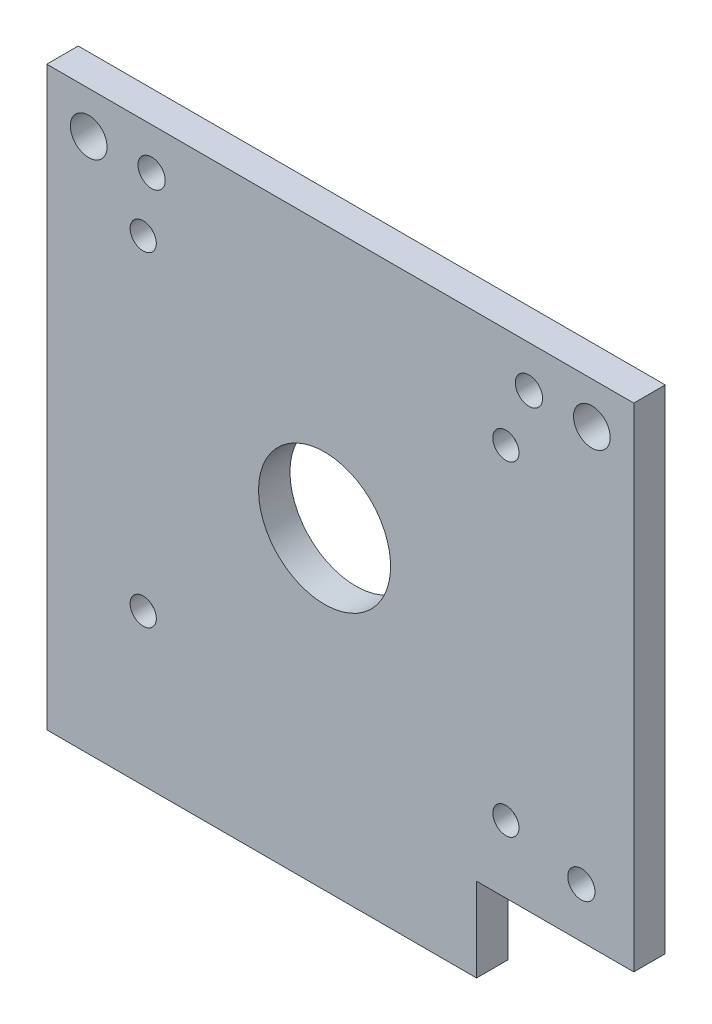
SolidWorks part; units mm, degrees
ref_plane "Alzado" through (0, 0, 0) normal (0, 0, 1) x (1, 0, 0)
ref_plane "Planta" through (0, 0, 0) normal (0, 1, 0) x (1, 0, 0)
ref_plane "Vista lateral" through (0, 0, 0) normal (1, 0, 0) x (0, 0, -1)
sketch "Croquis1" plane through (0, 0, 0) normal (0, 0, 1) x (1, 0, 0)
  line L5 (-26.5, -27.5) -> (29.5, -27.5)
  line L6 (-26.5, -27.5) -> (-26.5, 27.5)
  line L7 (-26.5, 27.5) -> (29.5, 27.5)
  line L8 (29.5, -27.5) -> (29.5, 27.5)
  line L9 (-26.5, -27.5) -> (29.5, 27.5) construction
  line L10 (-26.5, 27.5) -> (29.5, -27.5) construction
  point P0 (1.5, 0)
extrude "Saliente-Extruir1" add sketch "Croquis1" along normal blind 3
sketch "Croquis2" plane through (0, 0, 3) normal (0, 0, 1) x (1, 0, 0)
  line L0 (29.5, -27.5) -> (14.5, -27.5)
  line L1 (24.5, -14.75) -> (24.5, -27.5)
  line L2 (-26.5, -27.5) -> (29.5, -27.5) construction
  line L3 (24.5, -27.5) -> (29.5, -27.5)
  line L4 (25.5, 23.5288) -> (29.5, 23.5288)
  line L5 (25.5, 23.5288) -> (19.5, 23.5288)
  line L6 (29.5, -27.5) -> (29.5, 27.5) construction
  line L7 (-16.5, 23.5288) -> (-22.5, 23.5288)
  line L8 (-26.5, 27.5) -> (-26.5, -27.5) construction
  line L9 (14.5, -27.5) -> (14.5, -19.5)
  line L10 (14.5, -19.5) -> (29.5, -19.5)
  line L11 (29.5, -19.5) -> (29.5, -27.5)
  circle A3 centre (25.5, 23.5288) radius 1.75
  circle A4 centre (24.5, -14.75) radius 1.3
  circle A5 centre (19.5, 23.5288) radius 1.3
  circle A6 centre (-16.5, 23.5288) radius 1.3
  circle A7 centre (-22.5, 23.5288) radius 1.75
  circle A8 centre (19.5, 23.5288) radius 2.5
  dimension "D1" = 4
  dimension "D2" = 15
  dimension "D4" = 5
  dimension "D3" = 8
extrude "Cortar-Extruir1" cut sketch "Croquis2" against normal blind 4
sketch "Croquis3" plane through (0, 0, 0) normal (0, 0, -1) x (-1, 0, 0)
  circle A0 centre (0, 2.415) radius 6.3
extrude "Cortar-Extruir2" cut sketch "Croquis3" against normal up to next
sketch "Croquis4" plane through (0, 0, 3) normal (0, 0, 1) x (1, 0, 0)
  line L1 (-17.3, -13.085) -> (17.3, -13.085) construction
  line L2 (-17.3, -13.085) -> (-17.3, 17.915) construction
  line L3 (-17.3, 17.915) -> (17.3, 17.915) construction
  line L4 (17.3, -13.085) -> (17.3, 17.915) construction
  line L5 (-17.3, -13.085) -> (17.3, 17.915) construction
  line L6 (-17.3, 17.915) -> (17.3, -13.085) construction
  circle A0 centre (-17.3, 17.915) radius 1.25
  circle A1 centre (17.3, 17.915) radius 1.25
  circle A2 centre (-17.3, -13.085) radius 1.25
  circle A3 centre (17.3, -13.085) radius 1.25
  point P0 (0, 2.415)
  dimension "D3" = 2.5
  dimension "D4" = 2.5
  dimension "D5" = 2.5
  dimension "D6" = 2.5
  dimension "D1" = 34.6
  dimension "D2" = 31
extrude "Cortar-Extruir3" cut sketch "Croquis4" against normal blind 10
chamfer "Chaflán2" distance 1.25 angle 45 4 edges at (16.05, -13.085, 0) (-18.55, -13.085, 0) (-18.55, 17.915, 0) (16.05, 17.915, 0)
